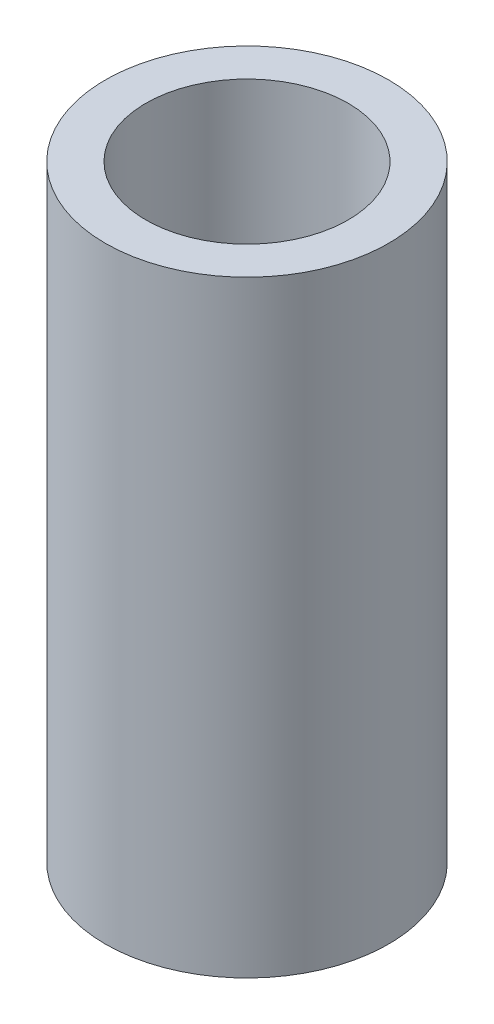
SolidWorks part; units mm, degrees
material "ABS"
ref_plane "Front Plane" through (0, 0, 0) normal (0, 0, 1) x (1, 0, 0)
ref_plane "Top Plane" through (0, 0, 0) normal (0, 1, 0) x (1, 0, 0)
ref_plane "Right Plane" through (0, 0, 0) normal (1, 0, 0) x (0, 0, -1)
sketch "Sketch1" plane through (0, 0, 0) normal (0, 1, 0) x (1, 0, 0)
  circle A0 centre (0, 0) radius 4.445
  circle A1 centre (0, 0) radius 3.175
  dimension "D1" = 8.89
  dimension "D2" = 6.35
extrude "Boss-Extrude1" add sketch "Sketch1" along normal blind 19.05
